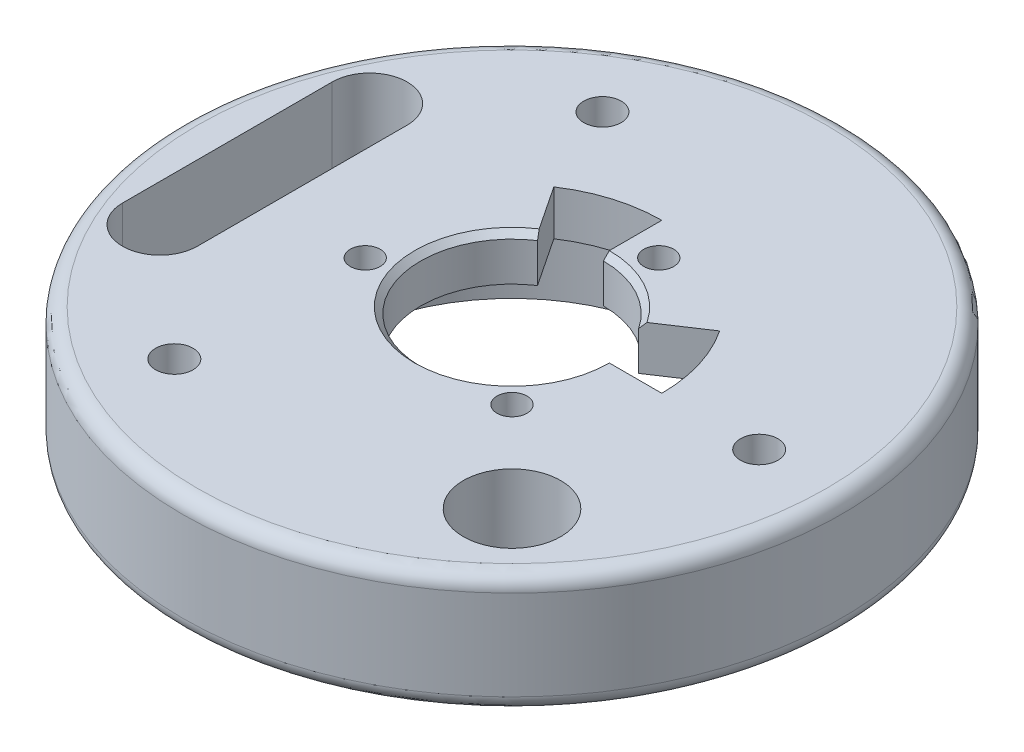
SolidWorks part; units mm, degrees
material "Brass"
ref_plane "Front Plane" through (0, 0, 0) normal (0, 0, 1) x (1, 0, 0)
ref_plane "Top Plane" through (0, 0, 0) normal (0, 1, 0) x (1, 0, 0)
ref_plane "Right Plane" through (0, 0, 0) normal (1, 0, 0) x (0, 0, -1)
sketch "Sketch1" plane through (0, 0, 0) normal (0, 0, 1) x (1, 0, 0)
  line L0 (0, 0) -> (0, 59.9431) construction
  line L1 (6.1, 0) -> (6.1, 59.9431) construction
  line L2 (0, 0) -> (12, 0) construction
  line L3 (12, 0) -> (12, 4)
  line L4 (12, 4) -> (13, 4)
  line L5 (13, 4) -> (13, 5)
  line L6 (13, 5) -> (6.1, 5)
  line L7 (6.1, 5) -> (6.1, 8)
  line L8 (6.1, 8) -> (22, 8)
  line L9 (12, 0) -> (22, 0)
  line L10 (22, 0) -> (22, 8)
  dimension "D1" = 6.1
  dimension "D2" = 4
  dimension "D3" = 1
  dimension "D4" = 3
  dimension "D5" = 1
  dimension "D6" = 22
revolve "Revolve1" add sketch "Sketch1" angle 360 about L0
fillet "Fillet2" radius 1 2 edges at (0, 0, -22) (0, 8, -22)
chamfer "Chamfer2" distance 0.4 angle 45 1 edges at (0, 8, -6.1)
sketch "Sketch3" plane through (0, 8, 0) normal (0, 1, 0) x (1, 0, 0)
  line L0 (0, 0) -> (8.3279, 5.5359)
  line L1 (0, 0) -> (10, 0)
  line L2 (0, 0) -> (2.0706, 7.7274) construction
  line L3 (0, 0) -> (-27.1322, 0) construction
  line L4 (-16.5, 0) -> (-16.5, 7) construction
  line L5 (-19, 7) -> (-19, -7)
  line L6 (-16.5, 7) -> (-19, 7) construction
  line L7 (-14, 7) -> (-14, -7)
  line L8 (0, 0) -> (31.166, 8.3509) construction
  line L9 (-5.5359, 8.3279) -> (0, 0) construction
  line L10 (0, 10) -> (0, 0) construction
  line L11 (0, 0) -> (0, 10) [skipped]
  line L12 (0, 0) -> (-5.5359, 8.3279) [skipped]
  line L13 (-5.5359, 8.3279) -> (-3.0646, 4.6102)
  line L14 (0, 10) -> (0, 5.5359)
  arc A0 (10, 0) -> (8.3279, 5.5359) centre (0, 0) ccw
  circle A1 centre (0, 0) radius 10 construction
  circle A2 centre (2.0706, 7.7274) radius 1
  circle A3 centre (0, 0) radius 8 construction
  circle A4 centre (5.6569, -5.6569) radius 1
  circle A5 centre (-7.7274, -2.0706) radius 1
  circle A6 centre (0, 0) radius 16.5 construction
  circle A7 centre (16.5, 0) radius 1.25
  circle A8 centre (-8.25, -14.2894) radius 1.25
  circle A9 centre (-8.25, 14.2894) radius 1.25
  arc A10 (-19, 7) -> (-14, 7) centre (-16.5, 7) cw
  arc A11 (-19, -7) -> (-14, -7) centre (-16.5, -7) ccw
  arc A12 (0, 10) -> (-5.5359, 8.3279) centre (0, 0) ccw
  arc A13 (15.9378, 4.2705) -> (11.6673, -11.6673) centre (0, 0) cw construction
  circle A14 centre (11.6673, -11.6673) radius 3.25
  arc A15 (0, 5.5359) -> (-3.0646, 4.6102) centre (0, 0) ccw
  point P15 (0, 0)
  point P23 (0, 0)
  point P29 (-14, 0)
  point P31 (-19, 0)
  point P39 (0, 0)
  dimension "D1" = 3
  dimension "D2" = 75
  dimension "D3" = 3
  dimension "D4" = 2
  dimension "D5" = 16.5
extrude "Cut-Extrude1" cut sketch "Sketch3" against normal blind 10
